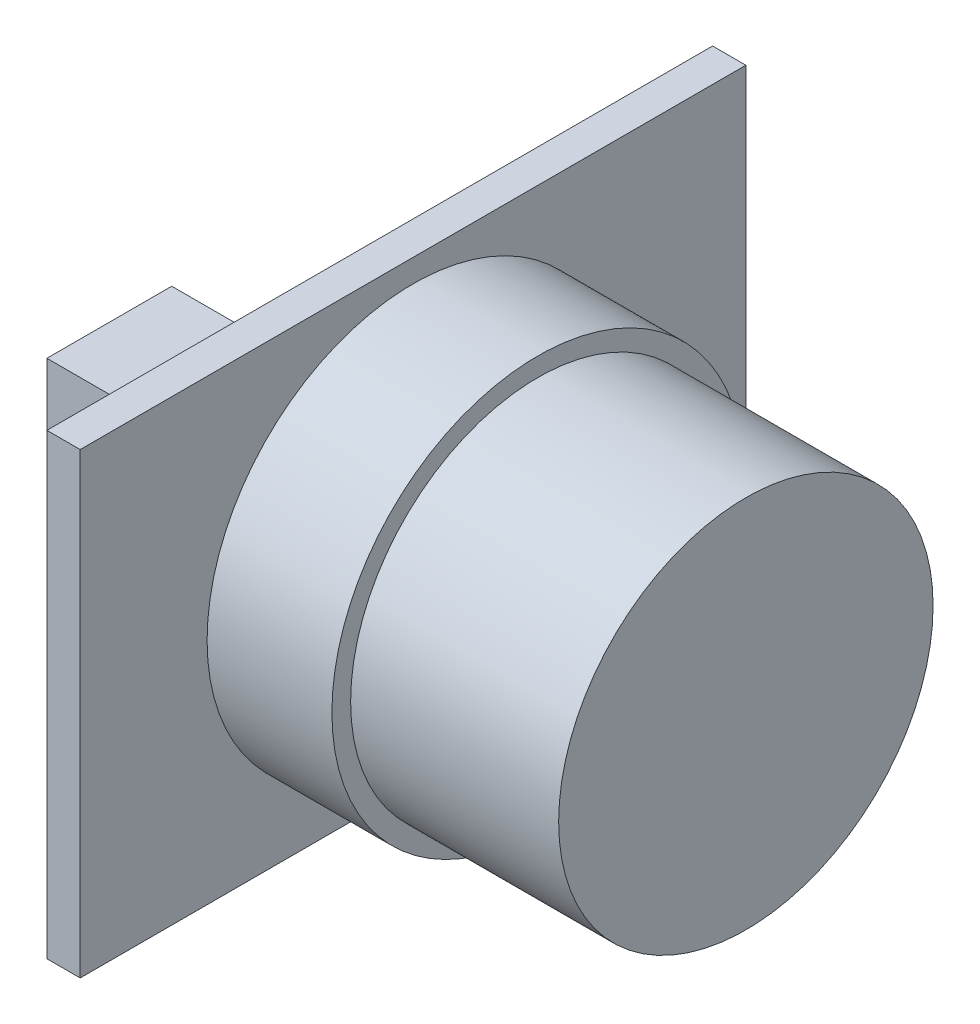
SolidWorks part; units mm, degrees
ref_plane "Front Plane" through (0, 0, 0) normal (0, 0, 1) x (1, 0, 0)
ref_plane "Top Plane" through (0, 0, 0) normal (0, 1, 0) x (1, 0, 0)
ref_plane "Right Plane" through (0, 0, 0) normal (1, 0, 0) x (0, 0, -1)
ref_plane "Plane1" through (0, 0, 9) normal (0, 0, 1) x (1, 0, 0)
sketch "Sketch1" plane through (0, 0, 9) normal (0, 0, 1) x (1, 0, 0)
  line L1 (29.2, -132.5) -> (30.8, -132.5)
  line L2 (29.2, -132.5) -> (29.2, -110.5)
  line L3 (29.2, -110.5) -> (30.8, -110.5)
  line L4 (30.8, -132.5) -> (30.8, -110.5)
  line L5 (29.2, -132.5) -> (30.8, -110.5) construction
  line L6 (29.2, -110.5) -> (30.8, -132.5) construction
  point P0 (30, -121.5)
extrude "Boss-Extrude1" add sketch "Sketch1" along normal blind 32
ref_plane "Plane2" through (30.8, 0, 0) normal (1, 0, 0) x (0, 0, -1)
sketch "Sketch2" plane through (30.8, 0, 0) normal (1, 0, 0) x (0, 0, -1)
  circle A0 centre (-25, -121.5) radius 9.9
extrude "Boss-Extrude2" add sketch "Sketch2" along normal blind 6
ref_plane "Plane3" through (36.8, 0, 0) normal (1, 0, 0) x (0, 0, -1)
sketch "Sketch3" plane through (36.8, 0, 0) normal (1, 0, 0) x (0, 0, -1)
  circle A0 centre (-25, -121.5) radius 9
extrude "Boss-Extrude3" add sketch "Sketch3" along normal blind 10
ref_plane "Plane4" through (0, 0, 29) normal (0, 0, 1) x (1, 0, 0)
sketch "Sketch4" plane through (0, 0, 29) normal (0, 0, 1) x (1, 0, 0)
  line L0 (29.2, -110.5) -> (29.2, -132.5) construction
  line L1 (23.2, -119.5) -> (29.2, -119.5)
  line L2 (23.2, -119.5) -> (23.2, -113.5)
  line L3 (23.2, -113.5) -> (29.2, -113.5)
  line L4 (29.2, -119.5) -> (29.2, -113.5)
  line L5 (23.2, -119.5) -> (29.2, -113.5) construction
  line L6 (23.2, -113.5) -> (29.2, -119.5) construction
  point P0 (26.2, -116.5)
extrude "Boss-Extrude4" add sketch "Sketch4" along normal blind 6
